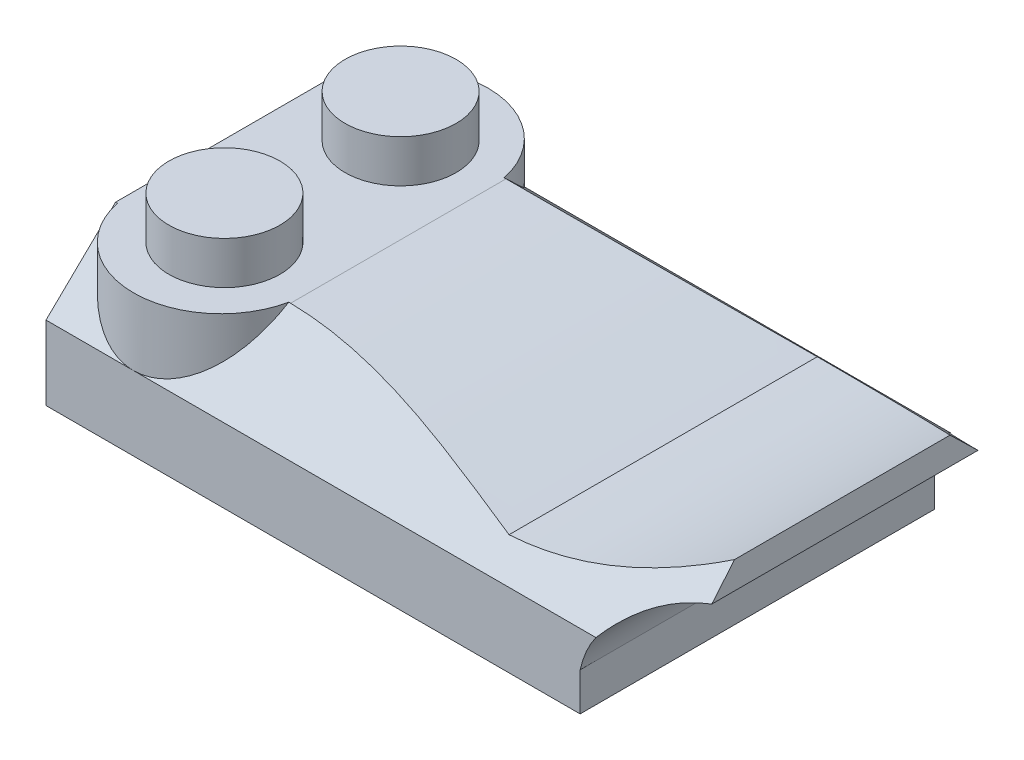
SolidWorks part; units mm, degrees
ref_plane "Front Plane" through (0, 0, 0) normal (0, 0, 1) x (1, 0, 0)
ref_plane "Top Plane" through (0, 0, 0) normal (0, 1, 0) x (1, 0, 0)
ref_plane "Right Plane" through (0, 0, 0) normal (1, 0, 0) x (0, 0, -1)
sketch "Sketch1" plane through (0, 0, 0) normal (0, 1, 0) x (1, 0, 0)
  line L0 (-34.029, 15.8) -> (-6.329, 15.8)
  line L1 (-6.329, 15.8) -> (-6.329, 0)
  line L2 (-6.329, 0) -> (-34.029, 0)
  line L3 (-34.029, 0) -> (-34.029, 15.8)
  dimension "D1" = 27.7
  dimension "D2" = 15.8
extrude "Boss-Extrude1" add sketch "Sketch1" along normal blind 6.3
sketch "Sketch2" plane through (0, 0, 0) normal (0, 0, 1) x (1, 0, 0)
  line L0 (-34.029, 0) -> (-10.229, 0)
  line L1 (-34.029, 0) -> (-6.329, 0) construction
  line L2 (-10.229, 0) -> (-10.229, 1.7)
  line L3 (-34.029, 0) -> (-34.029, 6.3)
  line L4 (-34.029, 6.3) -> (-26.229, 6.3)
  line L5 (-34.029, 6.3) -> (-6.329, 6.3) construction
  line L6 (-6.446, 6.3) -> (-6.329, 5.2062)
  line L7 (-6.329, 6.3) -> (-6.329, 0) construction
  spline S0 degree 3 poles (-26.229, 6.3) (-22.2059, 6.2705) (-18.301, 5.2554) (-14.429, 4.3) knots 0 0 0 0 1 1 1 1
  spline S1 degree 2 poles (-14.429, 4.3) (-10.2153, 4.423) (-6.446, 6.3) knots 0 0 0 1 1 1
  spline S2 degree 2 poles (-10.229, 1.7) (-9.6041, 4.4467) (-6.329, 5.2062) knots 0 0 0 1 1 1
  dimension "D1" = 23.8
  dimension "D2" = 7.8
  dimension "D3" = 4.2
  dimension "D4" = 4.3
  dimension "D5" = 1.1
  dimension "D6" = 1.7
extrude "Cut-Extrude1" cut sketch "Sketch2" against normal offset from surface (15.9 mm away) 15.9 flip side to cut up to face at (-20.179, 3.15, 0)
sketch "Sketch3" plane through (-34.029, 0, 0) normal (-1, 0, 0) x (0, 0, 1)
  line L0 (-15.8, 0) -> (-15.8, 3.3)
  line L1 (-15.8, 6.3) -> (-15.8, 0) construction
  line L2 (-15.8, 3.3) -> (-12.7, 6.3)
  line L3 (-15.8, 6.3) -> (0, 6.3) construction
  line L4 (-12.7, 6.3) -> (-3.1, 6.3)
  line L5 (-3.1, 6.3) -> (0, 3.3)
  line L6 (0, 6.3) -> (0, 0) construction
  line L7 (0, 3.3) -> (0, 0)
  line L8 (0, 0) -> (-15.8, 0)
  dimension "D1" = 3.3
  dimension "D2" = 3.3
  dimension "D3" = 9.6
  dimension "D4" = 3.1
extrude "Cut-Extrude2" cut sketch "Sketch3" against normal blind 35.9 flip side to cut
sketch "Sketch4" plane through (0, 0, 0) normal (0, -1, 0) x (1, 0, 0)
  line L0 (-34.029, -12.7) -> (-34.029, -3.1) construction
  line L2 (-34.029, -3.9) -> (-34.029, -11.9)
  line L3 (-26.229, -12.7) -> (-26.229, -3.1) construction
  line L4 (-26.229, -11.9) -> (-26.229, -3.9)
  line L5 (-9.5254, -15.8) -> (-34.029, -15.8) construction
  arc A0 (-34.029, -3.9) -> (-26.229, -3.9) centre (-30.129, -3.9) cw
  arc A1 (-34.029, -11.9) -> (-26.229, -11.9) centre (-30.129, -11.9) ccw
  dimension "D1" = 3.9
  dimension "D2" = 3.9
  dimension "D3" = 8
  dimension "D4" = 3.9
extrude "Boss-Extrude2" add sketch "Sketch4" against normal blind 6.3
sketch "Sketch5" plane through (0, 6.3, 0) normal (0, 1, 0) x (1, 0, 0)
  line L0 (-34.029, 12.7) -> (-34.029, 3.1) construction
  circle A0 centre (-30.054, 11.8257) radius 2.475
  circle A1 centre (-30.054, 3.975) radius 2.475
  arc A2 (-26.3119, 12.7) -> (-33.946, 12.7) centre (-30.129, 11.9) ccw construction
  point P6 (-30.129, 15.8)
  dimension "D5" = 4.95
  dimension "D6" = 4.95
  dimension "D1" = 3.975
  dimension "D2" = 3.975
  dimension "D3" = 3.975
  dimension "D4" = 3.975
extrude "Boss-Extrude3" add sketch "Sketch5" along normal blind 1.9
sketch "Sketch6" plane through (0, 0, 0) normal (0, -1, 0) x (1, 0, 0)
  line L0 (-32.529, -1.5) -> (-11.729, -1.5)
  line L1 (-11.729, -1.5) -> (-11.729, -14.3)
  line L2 (-11.729, -14.3) -> (-32.529, -14.3)
  line L3 (-32.529, -14.3) -> (-32.529, -1.5)
  line L4 (-34.029, 0) -> (-10.229, 0) construction
  line L5 (-34.029, -15.8) -> (-34.029, 0) construction
  line L6 (-10.229, -15.8) -> (-34.029, -15.8) construction
  line L7 (-10.229, -15.8) -> (-10.229, 0) construction
  dimension "D1" = 1.5
  dimension "D2" = 1.5
  dimension "D3" = 1.5
  dimension "D4" = 1.5
extrude "Cut-Extrude3" cut sketch "Sketch6" against normal blind 2
